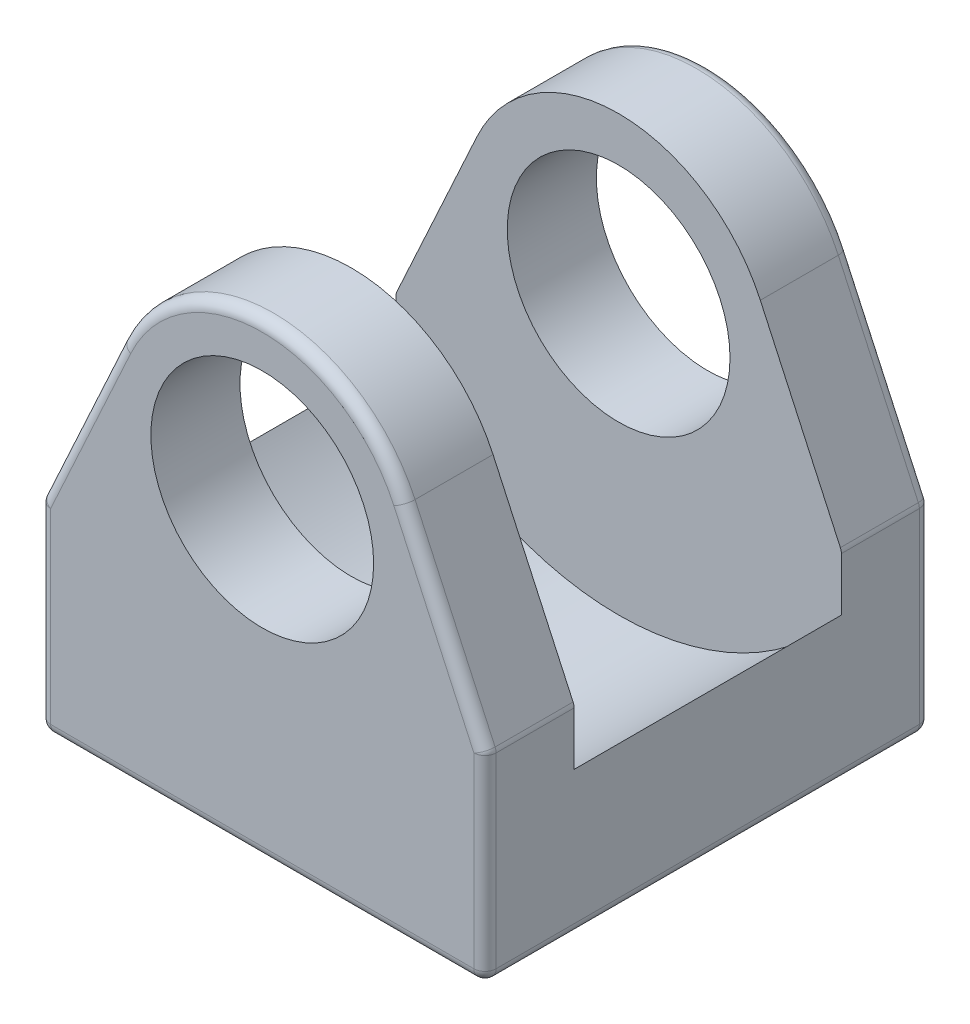
SolidWorks part; units mm, degrees
ref_plane "前视基准面" through (0, 0, 0) normal (0, 0, 1) x (1, 0, 0)
ref_plane "上视基准面" through (0, 0, 0) normal (0, 1, 0) x (1, 0, 0)
ref_plane "右视基准面" through (0, 0, 0) normal (1, 0, 0) x (0, 0, -1)
other "Configuration Table"
sketch "草图1" plane through (0, 0, 0) normal (0, 0, 1) x (1, 0, 0)
  line L0 (6.361, 12.422) -> (10, 4.5)
  line L2 (-10, 4.5) -> (-10, -4.5)
  line L3 (-10, -4.5) -> (10, -4.5)
  line L4 (10, 4.5) -> (10, -4.5)
  line L5 (-10, 4.5) -> (10, -4.5) construction
  line L6 (-10, -4.5) -> (10, 4.5) construction
  line L7 (-10, 4.5) -> (-6.361, 12.422)
  arc A0 (6.361, 12.422) -> (-6.361, 12.422) centre (0, 9.5) ccw
  circle A1 centre (0, 9.5) radius 5
  point P0 (0, 0)
  dimension "D3" = 14
  dimension "D4" = 10
  dimension "D1" = 20
  dimension "D2" = 9
  dimension "D5" = 5
extrude "凸台-拉伸1" add sketch "草图1" along normal mid plane 20
fillet "圆角1" radius 0.5 16 edges at (0, 16.5, 10) (0, 16.5, -10) (8.1805, 8.461, 10) (8.1805, 8.461, -10) (10, 0, 10) (10, 4.5, 0) (10, 0, -10) (0, -4.5, 10) (10, -4.5, 0) (0, -4.5, -10) (-10, 0, 10) (-10, -4.5, 0) (-10, 0, -10) (-8.1805, 8.461, 10) (-10, 4.5, 0) (-8.1805, 8.461, -10)
sketch "草图3" plane through (0, 0, 0) normal (0, 0, 1) x (1, 0, 0)
  circle A0 centre (0, 9.5) radius 12.5
  dimension "D1" = 25
extrude "切除-拉伸1" cut sketch "草图3" against normal mid plane 12
